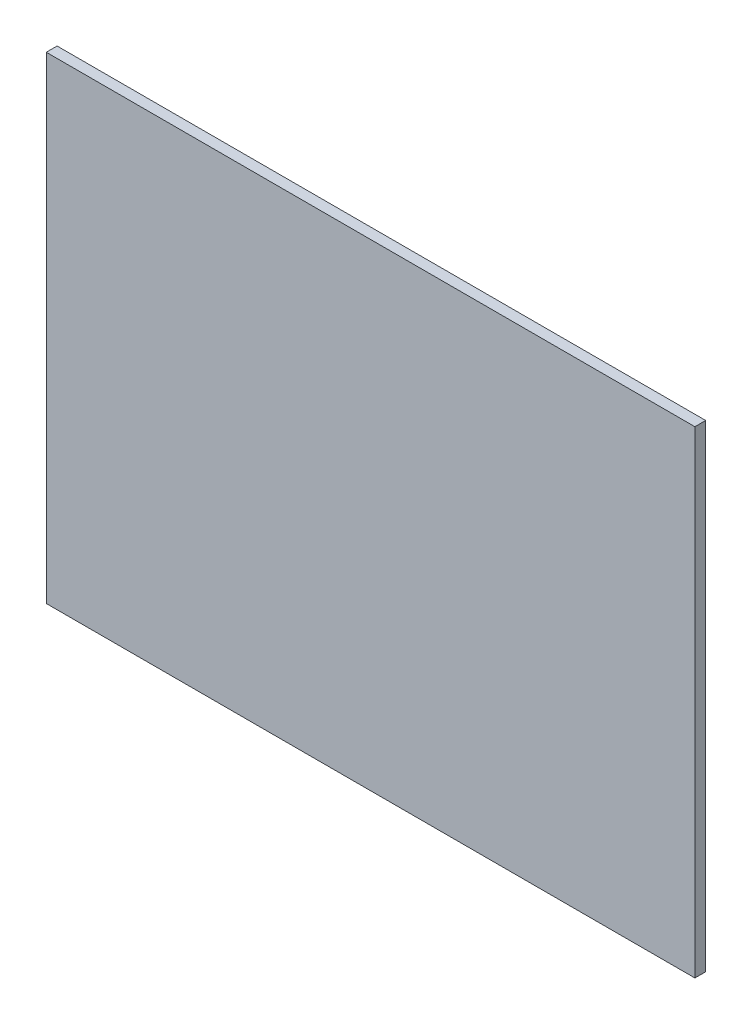
SolidWorks part; units mm, degrees
material "Plain Carbon Steel"
ref_plane "Front Plane" through (0, 0, 0) normal (0, 0, 1) x (1, 0, 0)
ref_plane "Top Plane" through (0, 0, 0) normal (0, 1, 0) x (1, 0, 0)
ref_plane "Right Plane" through (0, 0, 0) normal (1, 0, 0) x (0, 0, -1)
sketch "Sketch1" plane through (0, 0, 0) normal (0, 0, 1) x (1, 0, 0)
  line L1 (-90, -66.25) -> (90, -66.25)
  line L2 (-90, -66.25) -> (-90, 66.25)
  line L3 (-90, 66.25) -> (90, 66.25)
  line L4 (90, -66.25) -> (90, 66.25)
  line L5 (-90, -66.25) -> (90, 66.25) construction
  line L6 (-90, 66.25) -> (90, -66.25) construction
  point P0 (0, 0)
  dimension "D1" = 132.5
  dimension "D2" = 180
extrude "Boss-Extrude1" add sketch "Sketch1" along normal blind 3
